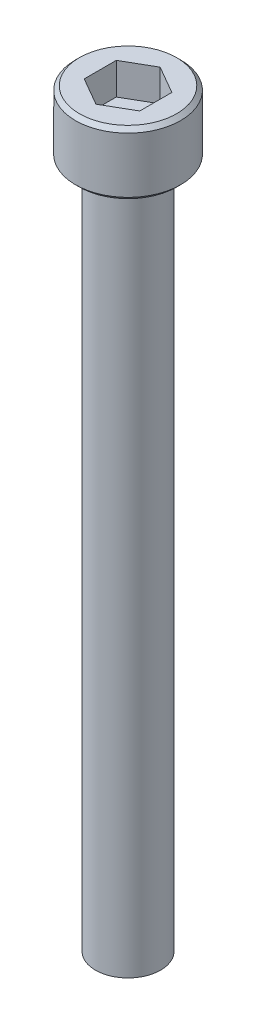
SolidWorks part; units mm, degrees
ref_plane "Front Plane" through (0, 0, 0) normal (0, 0, 1) x (1, 0, 0)
ref_plane "Top Plane" through (0, 0, 0) normal (0, 1, 0) x (1, 0, 0)
ref_plane "Right Plane" through (0, 0, 0) normal (1, 0, 0) x (0, 0, -1)
sketch "Sketch1" plane through (0, 0, 0) normal (0, 0, 1) x (1, 0, 0)
  line L0 (3.3655, 4.064) -> (0, 4.064)
  line L1 (0, 4.064) -> (0, 0)
  line L2 (0, 0) -> (3.3655, 0)
  line L3 (3.3655, 0) -> (3.3655, 4.064)
  line L4 (0, 4.064) -> (0, 0) construction
revolve "Revolve1" add sketch "Sketch1" angle 360 about L4
sketch "Sketch2" plane through (0, 0, 0) normal (0, -1, 0) x (1, 0, 0)
  circle A0 centre (0, 0) radius 2.0828
extrude "Boss-Extrude1" add sketch "Sketch2" along normal blind 44.45
sketch "Sketch3" plane through (0, 4.064, 0) normal (0, 1, 0) x (-1, 0, 0)
  line L0 (-1.778, -1.0265) -> (0, -2.0531)
  line L1 (0, -2.0531) -> (1.778, -1.0265)
  line L2 (1.778, -1.0265) -> (1.778, 1.0265)
  line L3 (1.778, 1.0265) -> (0, 2.0531)
  line L4 (0, 2.0531) -> (-1.778, 1.0265)
  line L5 (-1.778, 1.0265) -> (-1.778, -1.0265)
extrude "Cut-Extrude1" cut sketch "Sketch3" against normal blind 2.032
chamfer "Chamfer1" distance 0.254 angle 45 2 edges at (3.3655, 4.064, 0) (3.3655, 0, 0)
chamfer "Chamfer2" distance 0.7696 angle 34.979 1 edges at (2.0828, -44.45, 0)
